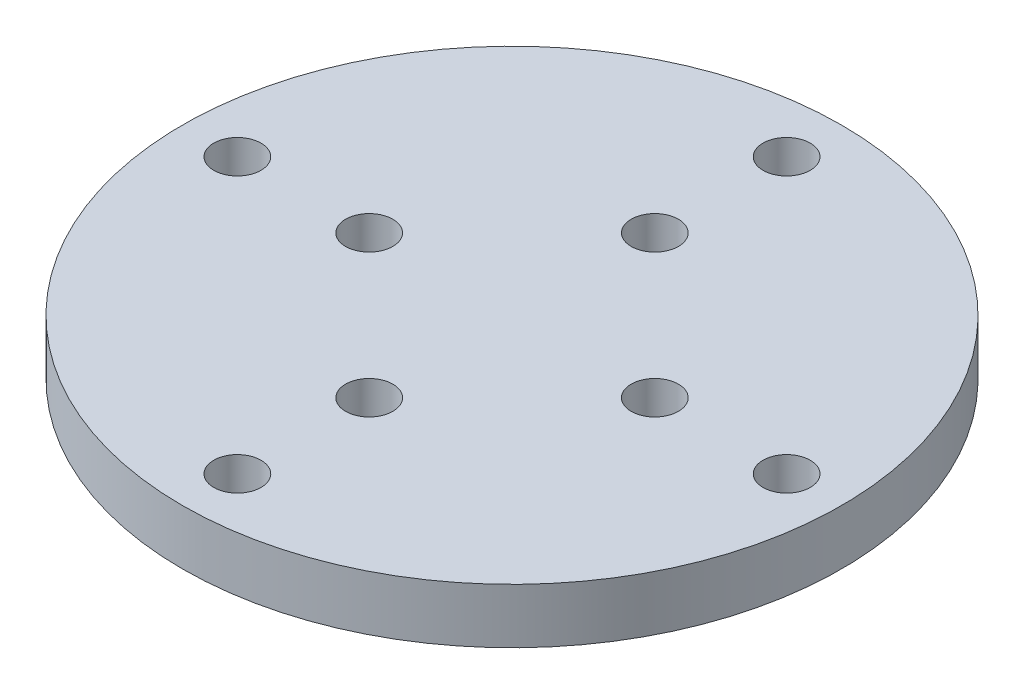
SolidWorks part; units mm, degrees
ref_plane "Front Plane" through (0, 0, 0) normal (0, 0, 1) x (1, 0, 0)
ref_plane "Top Plane" through (0, 0, 0) normal (0, 1, 0) x (1, 0, 0)
ref_plane "Right Plane" through (0, 0, 0) normal (1, 0, 0) x (0, 0, -1)
sketch "Sketch1" plane through (0, 0, 0) normal (0, 1, 0) x (1, 0, 0)
  circle A0 centre (0, 0) radius 30
  dimension "D1" = 60
extrude "Boss-Extrude1" add sketch "Sketch1" along normal blind 5
hole_wizard "M4 Clearance Hole1" positions "Sketch3" profile "Sketch2" hole size "M4" standard "ISO" end condition through all
sketch "Sketch3" plane through (0, 5, 0) normal (0, 1, 0) x (1, 0, 0)
  point P0 (0, -25)
  point P2 (-25, 0)
  point P4 (25, 0)
  point P6 (0, 25)
  dimension "D1" = 25
  dimension "D2" = 25
  dimension "D3" = 25
  dimension "D4" = 25
sketch "Sketch2" plane through (0, 5, 25) normal (1, 0, 0) x (0, 0, 1)
  line L0 (0, 0) -> (0, 5)
  line L1 (0, 5) -> (2.15, 5)
  line L2 (2.15, 5) -> (2.15, 0)
  line L5 (2.15, 0) -> (0, 0)
  line L11 (0, -6.35) -> (0, 107.95) construction
  dimension "Thru Hole Dia." = 4.3
  dimension "Thru Hole Depth" = 5
hole_wizard "M4 Clearance Hole2" positions "Sketch5" profile "Sketch4" hole size "M4" standard "ISO" end condition through all
sketch "Sketch5" plane through (0, 5, 0) normal (0, 1, 0) x (1, 0, 0)
  point P0 (-13, 0)
  point P2 (13, 0)
  point P4 (0, 13)
  point P6 (0, -13)
  dimension "D1" = 13
  dimension "D2" = 13
  dimension "D3" = 13
  dimension "D4" = 13
sketch "Sketch4" plane through (-13, 5, 0) normal (1, 0, 0) x (0, 0, 1)
  line L0 (0, 0) -> (0, 5)
  line L1 (0, 5) -> (2.15, 5)
  line L2 (2.15, 5) -> (2.15, 0)
  line L5 (2.15, 0) -> (0, 0)
  line L11 (0, -6.35) -> (0, 107.95) construction
  dimension "Thru Hole Dia." = 4.3
  dimension "Thru Hole Depth" = 5
